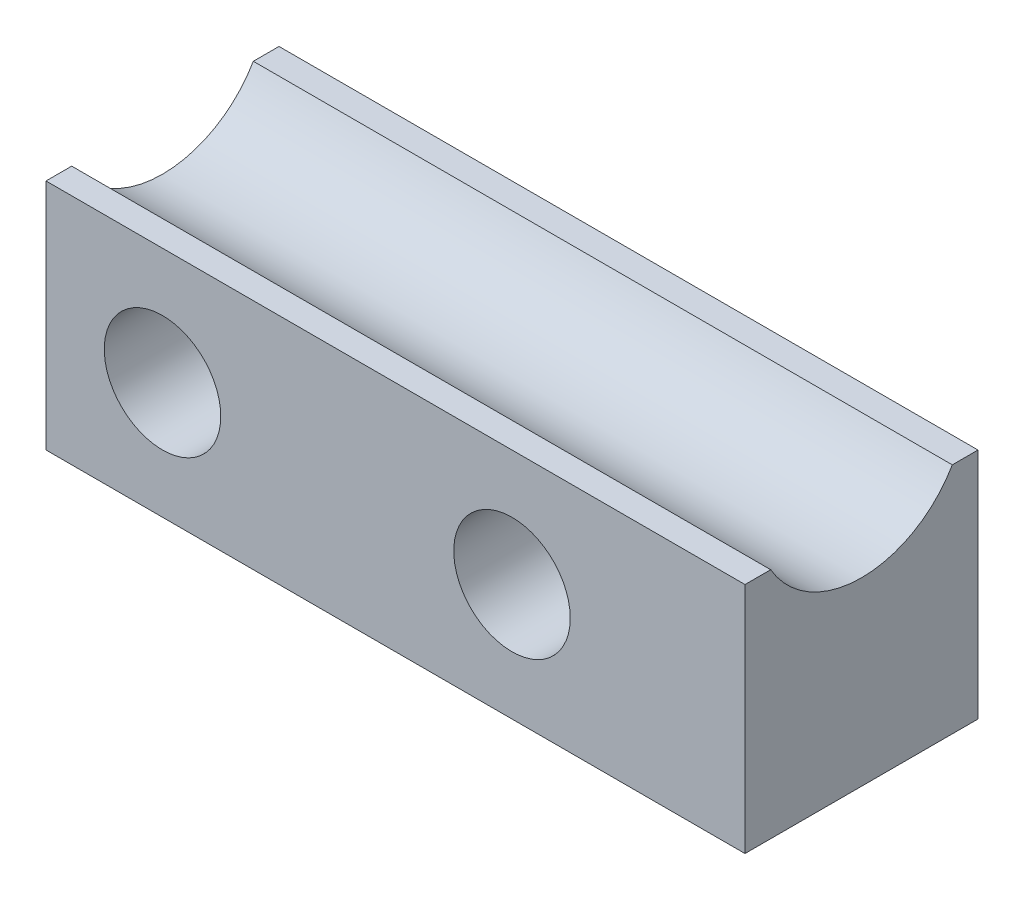
SolidWorks part; units mm, degrees
ref_plane "前基準面" through (0, 0, 0) normal (0, 0, 1) x (1, 0, 0)
ref_plane "上基準面" through (0, 0, 0) normal (0, 1, 0) x (1, 0, 0)
ref_plane "右基準面" through (0, 0, 0) normal (1, 0, 0) x (0, 0, -1)
sketch "草圖1" plane through (0, 0, 0) normal (0, 0, 1) x (1, 0, 0)
  line L0 (-15, 0) -> (15, 0) construction
  line L1 (-15, -5) -> (15, -5)
  line L2 (-15, -5) -> (-15, 5)
  line L3 (-15, 5) -> (15, 5)
  line L4 (15, -5) -> (15, 5)
  line L5 (-15, -5) -> (15, 5) construction
  line L6 (-15, 5) -> (15, -5) construction
  circle A0 centre (-10, 0) radius 2.5
  circle A1 centre (5, 0) radius 2.5
  point P0 (0, 0)
  dimension "D3" = 5
  dimension "D4" = 5
  dimension "D1" = 10
  dimension "D2" = 30
  dimension "D5" = 5
  dimension "D6" = 10
extrude "填料-伸長1" add sketch "草圖1" along normal blind 10
sketch "草圖2" plane through (15, 0, 0) normal (1, 0, 0) x (0, 0, -1)
  line L0 (-10, 5) -> (0, 5) construction
  circle A0 centre (-5, 7.25) radius 4.5
  point P4 (0, 0)
  point P5 (-5, 5)
  dimension "D1" = 9
  dimension "D2" = 2.25
extrude "除料-伸長1" cut sketch "草圖2" against normal up to next
